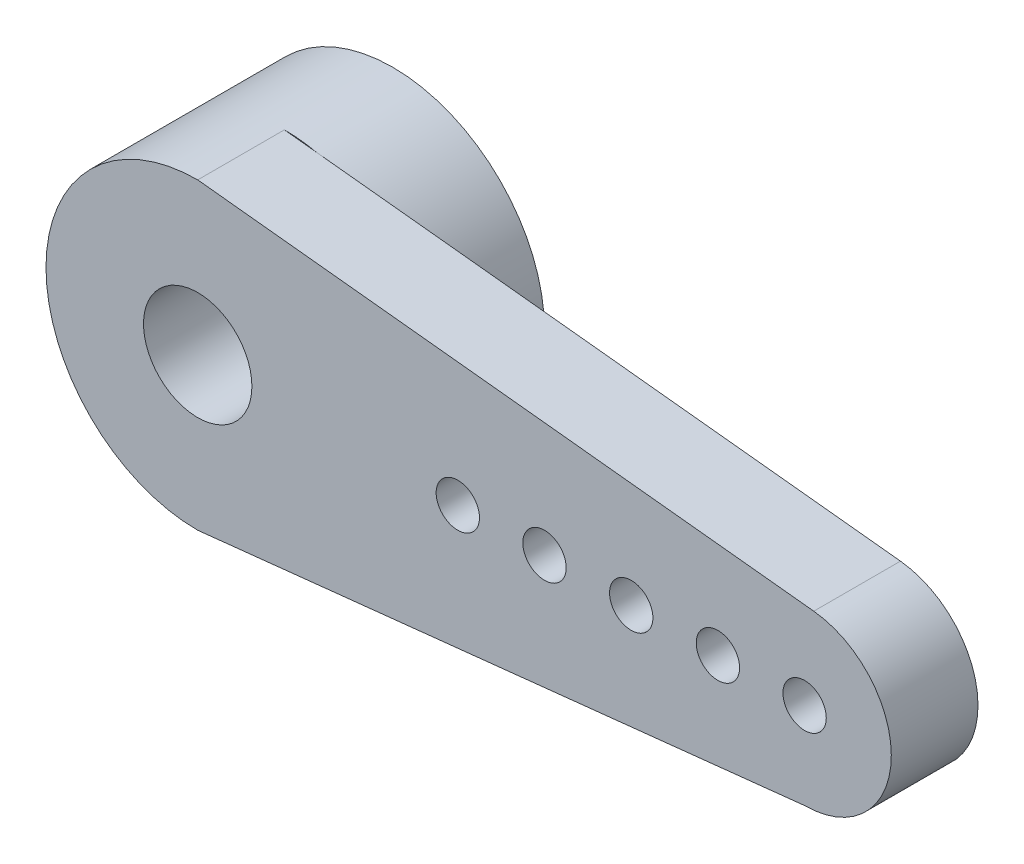
SolidWorks part; units mm, degrees
ref_plane "前基準面" through (0, 0, 0) normal (0, 0, 1) x (1, 0, 0)
ref_plane "上基準面" through (0, 0, 0) normal (0, 1, 0) x (1, 0, 0)
ref_plane "右基準面" through (0, 0, 0) normal (1, 0, 0) x (0, 0, -1)
sketch "草圖1" plane through (0, 0, 0) normal (0, 0, 1) x (1, 0, 0)
  line L0 (0, 3.5) -> (14.2115, 1.9888)
  line L1 (0, -3.5) -> (14, -2)
  arc A0 (0, 3.5) -> (0, -3.5) centre (0, 0) ccw
  arc A1 (14, -2) -> (14.2115, 1.9888) centre (14, 0) ccw
  circle A2 centre (0, 0) radius 1.25
  circle A3 centre (14, 0) radius 0.5
  dimension "D1" = 7
  dimension "D2" = 4
  dimension "D4" = 2.5
  dimension "D5" = 1
  dimension "D3" = 14
extrude "填料-伸長1" add sketch "草圖1" along normal blind 2
sketch "草圖2" plane through (0, 0, 2) normal (0, 0, 1) x (1, 0, 0)
  circle A0 centre (12, 0) radius 0.5
  circle A1 centre (10, 0) radius 0.5
  circle A2 centre (8, 0) radius 0.5
  circle A3 centre (6, 0) radius 0.5
  circle A4 centre (14, 0) radius 0.5 construction
  dimension "D5" = 1
  dimension "D6" = 1
  dimension "D7" = 1
  dimension "D8" = 1
  dimension "D1" = 2
  dimension "D2" = 2
  dimension "D3" = 2
  dimension "D4" = 2
extrude "除料-伸長1" cut sketch "草圖2" against normal up to next
sketch "草圖3" plane through (0, 0, 0) normal (0, 0, -1) x (-1, 0, 0)
  circle A0 centre (0, 0) radius 3.5
  circle A1 centre (0, 0) radius 2.5
  dimension "D1" = 7
  dimension "D2" = 5
extrude "填料-伸長2" add sketch "草圖3" along normal blind 2.5
